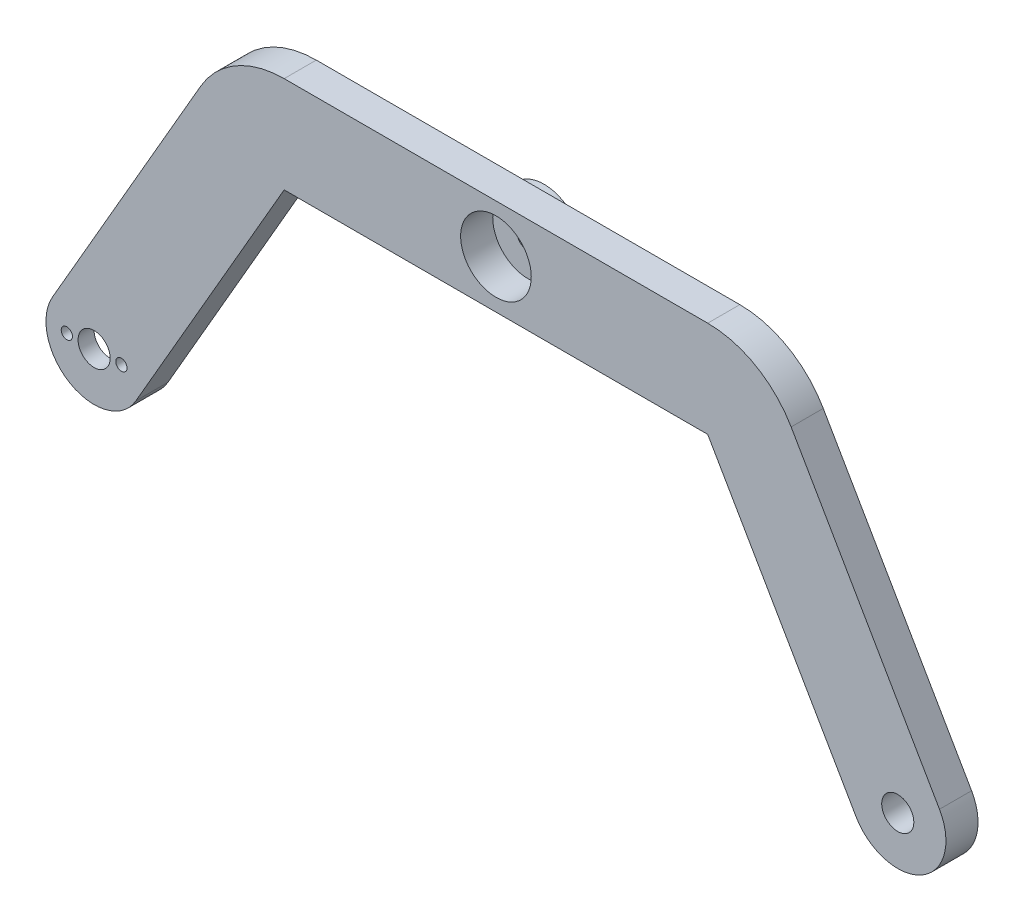
SolidWorks part; units mm, degrees
ref_plane "Front Plane" through (0, 0, 0) normal (0, 0, 1) x (1, 0, 0)
ref_plane "Top Plane" through (0, 0, 0) normal (0, 1, 0) x (1, 0, 0)
ref_plane "Right Plane" through (0, 0, 0) normal (1, 0, 0) x (0, 0, -1)
sketch "Sketch1" plane through (0, 0, 0) normal (0, 0, 1) x (1, 0, 0)
  line L0 (0, -15) -> (0, 15) construction
  line L1 (65.9559, 15) -> (-65.9559, 15)
  line L2 (65.9559, -15) -> (-65.9559, -15)
  line L3 (-65.9559, -15) -> (-112.1545, -95.0183)
  line L5 (-138.1353, -80.0183) -> (-91.9367, 0)
  line L6 (138.1353, -80.0183) -> (91.9367, 0)
  line L8 (65.9559, -15) -> (112.1545, -95.0183)
  arc A1 (-91.9367, 0) -> (-65.9559, 15) centre (-65.9559, -15) cw
  arc A2 (91.9367, 0) -> (65.9559, 15) centre (65.9559, -15) ccw
  circle A3 centre (-125.1449, -87.5183) radius 15 construction
  arc A5 (-138.1353, -80.0183) -> (-112.1545, -95.0183) centre (-125.1449, -87.5183) ccw
  arc A6 (112.1545, -95.0183) -> (138.1353, -80.0183) centre (125.1449, -87.5183) ccw
  circle A7 centre (-133.6449, -87.5183) radius 1.75
  circle A8 centre (-116.6449, -87.5183) radius 1.75
  point P4 (0, 0)
  point P6 (0, 15)
  point P10 (0, -15)
  dimension "D2" = 3.5
  dimension "D4" = 3.5
  dimension "D1" = 30
  dimension "D3" = 120
extrude "Boss-Extrude1" add sketch "Sketch1" along normal blind 10
sketch "Sketch2" plane through (0, 0, 10) normal (0, 0, 1) x (1, 0, 0)
  circle A0 centre (0, 0) radius 11
  circle A1 centre (-125.1449, -87.5183) radius 5
  circle A2 centre (125.1449, -87.5183) radius 5
  dimension "D1" = 22
extrude "Cut-Extrude1" cut sketch "Sketch2" against normal up to surface (10 mm away) up to face at (-131.8949, -87.5183, 0)
sketch "Sketch3" plane through (0, 0, 0) normal (0, 0, -1) x (-1, 0, 0)
  circle A0 centre (0, 0) radius 12
extrude "Boss-Extrude2" add sketch "Sketch3" along normal blind 5
sketch "Sketch4" plane through (0, 0, 0) normal (0, 0, -1) x (-1, 0, 0)
  circle A0 centre (125.1449, -87.5183) radius 13
  dimension "D1" = 26
extrude "Cut-Extrude2" cut sketch "Sketch4" against normal offset from surface (5 mm away) 5 up to face at (11, 0, 10)
sketch "Sketch5" plane through (0, 0, 10) normal (0, 0, 1) x (1, 0, 0)
  circle A0 centre (0, 0) radius 3.5
  dimension "D1" = 7
extrude "Cut-Extrude3" cut sketch "Sketch5" against normal through all
